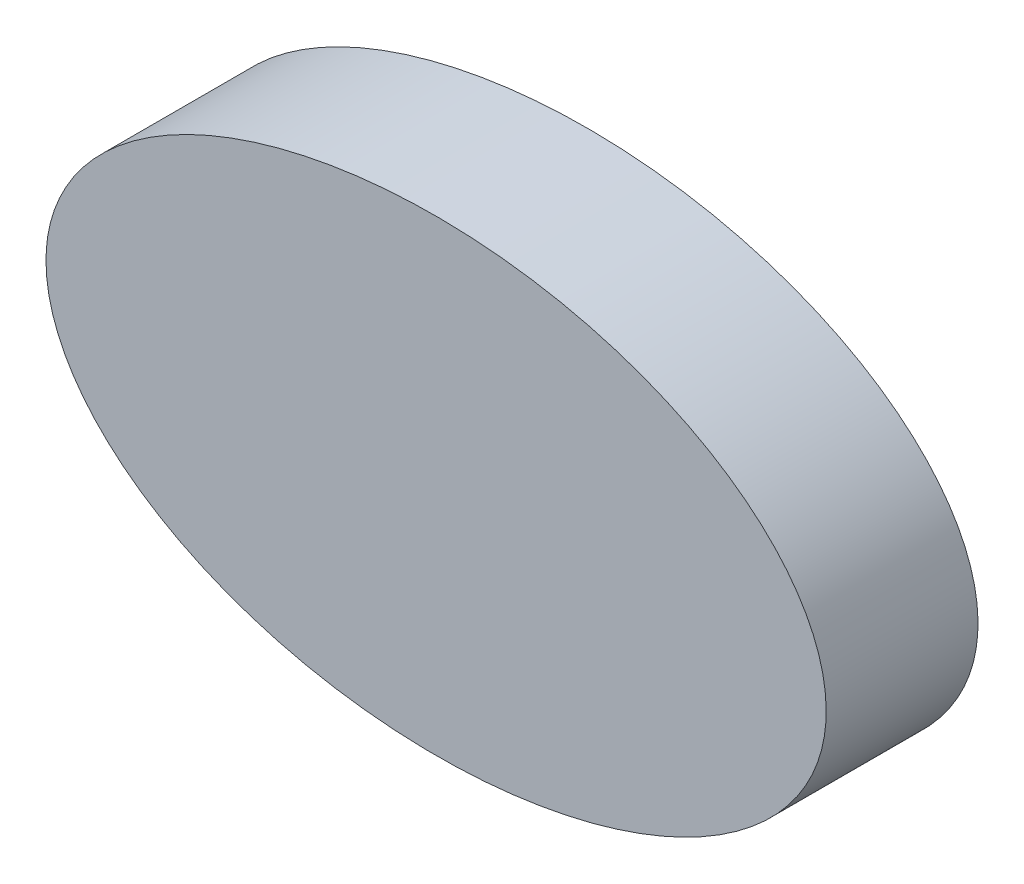
SolidWorks part; units mm, degrees
ref_plane "Plan de face" through (0, 0, 0) normal (0, 0, 1) x (1, 0, 0)
ref_plane "Plan de dessus" through (0, 0, 0) normal (0, 1, 0) x (1, 0, 0)
ref_plane "Plan de droite" through (0, 0, 0) normal (1, 0, 0) x (0, 0, -1)
sketch "Esquisse1" plane through (0, 0, 0) normal (0, 0, 1) x (1, 0, 0)
  ellipse E0 centre (0, 0) end of major axis (-42.418, 0) minor radius 25.4
extrude "Boss.-Extru.1" add sketch "Esquisse1" along normal blind 16.51
